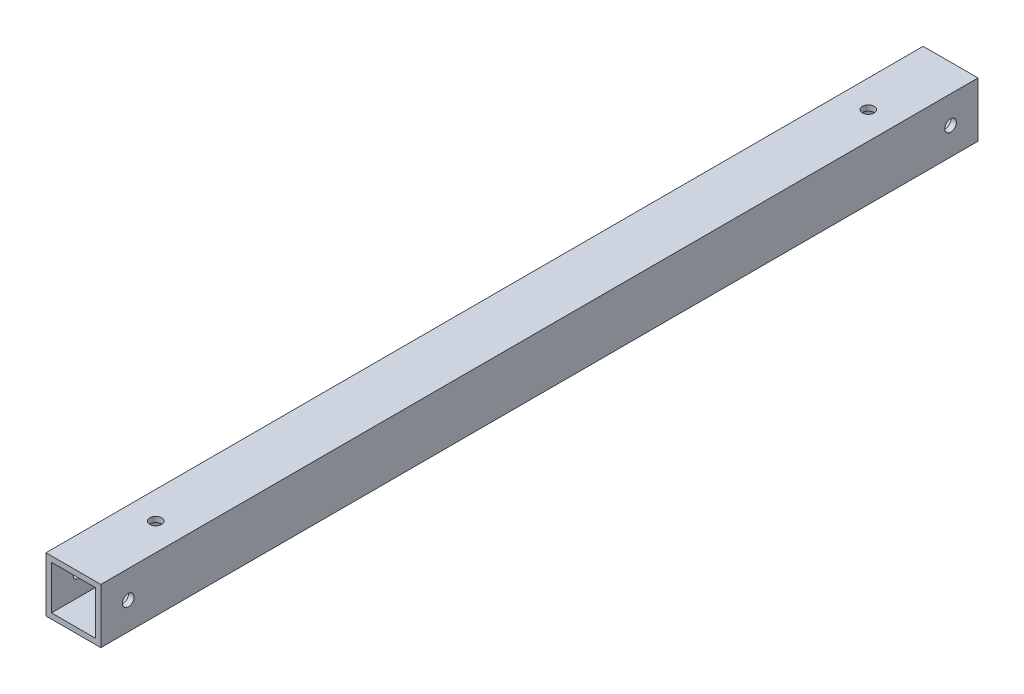
SolidWorks part; units mm, degrees
ref_plane "Front" through (0, 0, 0) normal (0, 0, 1) x (1, 0, 0)
ref_plane "Top" through (0, 0, 0) normal (0, 1, 0) x (1, 0, 0)
ref_plane "Right" through (0, 0, 0) normal (1, 0, 0) x (0, 0, -1)
sketch "ｽｹｯﾁ1" plane through (0, 0, 0) normal (0, 0, 1) x (1, 0, 0)
  line L0 (-6, 6) -> (6, 6)
  line L1 (-7.5, 7.5) -> (7.5, 7.5)
  line L2 (-7.5, 7.5) -> (-7.5, -7.5)
  line L3 (-7.5, -7.5) -> (7.5, -7.5)
  line L4 (7.5, 7.5) -> (7.5, -7.5)
  line L5 (0, -7.5) -> (0, 7.5) construction
  line L6 (-7.5, 0) -> (7.5, 0) construction
  line L7 (6, 6) -> (6, -6)
  line L8 (-6, -6) -> (6, -6)
  line L9 (-6, 6) -> (-6, -6)
  point P0 (0, 0)
  dimension "D1" = 15
  dimension "D2" = 15
  dimension "D3" = 1.5
extrude "ﾎﾞｽ - 押し出し1" add sketch "ｽｹｯﾁ1" along normal blind 240
sketch "ｽｹｯﾁ2" plane through (0, 7.5, 0) normal (0, 1, 0) x (1, 0, 0)
  line L0 (7.5, -240) -> (-7.5, -240) construction
  line L1 (7.5, -240) -> (7.5, 0) construction
  line L2 (7.5, 0) -> (-7.5, 0) construction
  circle A0 centre (0, -22.5) radius 1.6
  circle A1 centre (0, -217.5) radius 1.6
  dimension "D1" = 3.2
  dimension "D2" = 3.2
  dimension "D3" = 22.5
  dimension "D4" = 7.5
  dimension "D5" = 22.5
  dimension "D6" = 7.5
extrude "ｶｯﾄ - 押し出し1" cut sketch "ｽｹｯﾁ2" against normal through all
sketch "ｽｹｯﾁ3" plane through (7.5, 0, 0) normal (1, 0, 0) x (0, 0, -1)
  line L0 (-240, -7.5) -> (-240, 7.5) construction
  line L1 (0, -7.5) -> (0, 7.5) construction
  line L2 (-240, 7.5) -> (0, 7.5) construction
  circle A0 centre (-232.5, 0) radius 1.6
  circle A1 centre (-7.5, 0) radius 1.6
  dimension "D1" = 7.5
  dimension "D2" = 7.5
  dimension "D3" = 3.2
  dimension "D4" = 7.5
  dimension "D5" = 3.2
  dimension "D6" = 7.5
extrude "ｶｯﾄ - 押し出し2" cut sketch "ｽｹｯﾁ3" against normal through all
